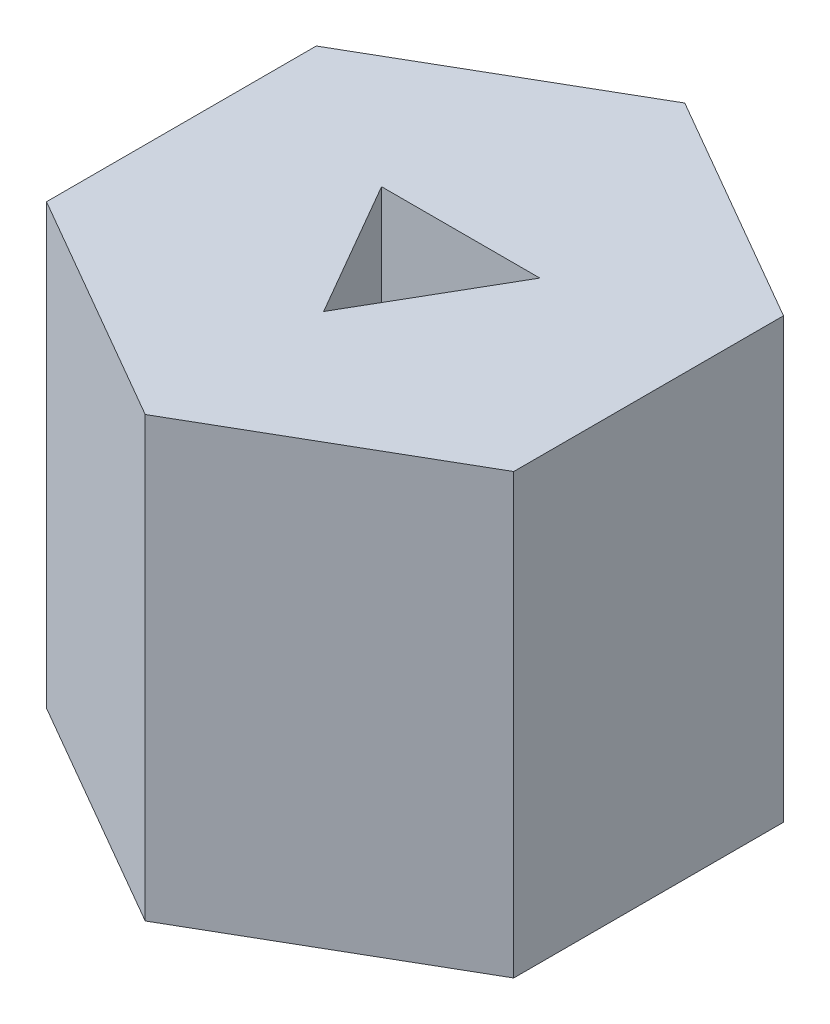
SolidWorks part; units mm, degrees
ref_plane "Front" through (0, 0, 0) normal (0, 0, 1) x (1, 0, 0)
ref_plane "Top" through (0, 0, 0) normal (0, 1, 0) x (1, 0, 0)
ref_plane "Right" through (0, 0, 0) normal (1, 0, 0) x (0, 0, -1)
sketch "Sketch1" plane through (0, 0, 0) normal (0, 1, 0) x (1, 0, 0)
  line L1 (0, 7.38) -> (-6.3913, 3.69)
  line L2 (-6.3913, 3.69) -> (-6.3913, -3.69)
  line L3 (-6.3913, -3.69) -> (0, -7.38)
  line L4 (0, -7.38) -> (6.3913, -3.69)
  line L5 (6.3913, -3.69) -> (6.3913, 3.69)
  line L6 (6.3913, 3.69) -> (0, 7.38)
  circle A0 centre (0, 0) radius 6.3913 construction
  dimension "D1" = 7.38
extrude "Boss-Extrude1" add sketch "Sketch1" along normal blind 12
sketch "Sketch2" plane through (0, 0, 0) normal (0, -1, 0) x (1, 0, 0)
  line L0 (0, 2.5) -> (-2.1651, -1.25)
  line L1 (-2.1651, -1.25) -> (2.1651, -1.25)
  line L2 (2.1651, -1.25) -> (0, 2.5)
  circle A0 centre (0, 0) radius 2.5
  dimension "D1" = 5
  dimension "D2" = 60
extrude "Cut-Extrude1" cut sketch "Sketch2" against normal blind 20 contours L1 L2 L0
